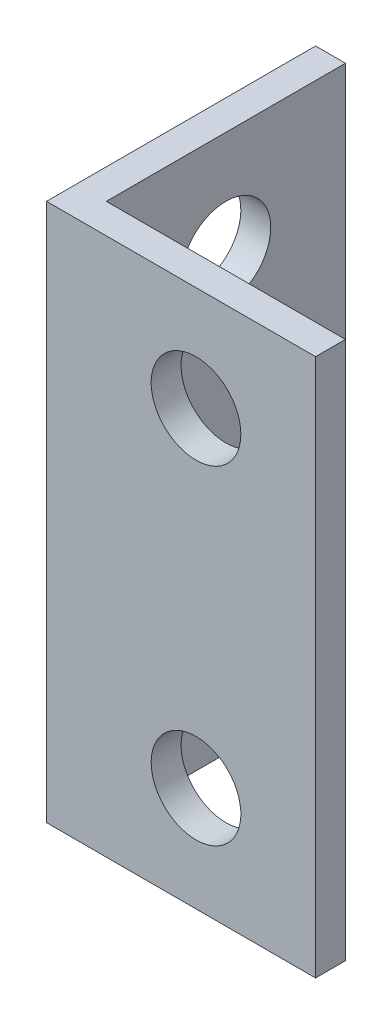
SolidWorks part; units mm, degrees
ref_plane "Plan de face" through (0, 0, 0) normal (0, 0, 1) x (1, 0, 0)
ref_plane "Plan de dessus" through (0, 0, 0) normal (0, 1, 0) x (1, 0, 0)
ref_plane "Plan de droite" through (0, 0, 0) normal (1, 0, 0) x (0, 0, -1)
sketch "Esquisse1" plane through (0, 0, 0) normal (0, 0, 1) x (1, 0, 0)
  line L0 (0, 10.3156) -> (0, -3.6144) construction
  line L1 (-4, 18) -> (4, 18)
  line L2 (-4, 18) -> (-4, 0)
  line L3 (-4, 0) -> (4, 0)
  line L4 (4, 18) -> (4, 0)
  dimension "D1" = 8
  dimension "D2" = 18
extrude "Boss.-Extru.1" add sketch "Esquisse1" along normal blind 1
sketch "Esquisse2" plane through (0, 0, 1) normal (0, 0, 1) x (1, 0, 0)
  line L1 (-4, 18) -> (-5, 18)
  line L2 (-4, 18) -> (-4, 0)
  line L3 (-4, 0) -> (-5, 0)
  line L4 (-5, 18) -> (-5, 0)
  dimension "D1" = 1
extrude "Boss.-Extru.2" add sketch "Esquisse2" against normal blind 9
sketch "Esquisse3" plane through (-4, 0, 0) normal (1, 0, 0) x (0, 0, -1)
  line L0 (4, 18) -> (4, -3.6029) construction
  line L1 (8, 18) -> (0, 18) construction
  line L2 (8, 9) -> (0, 9) construction
  line L3 (8, 0) -> (8, 18) construction
  line L4 (0, 0) -> (0, 18) construction
  circle A0 centre (4, 14.5) radius 1.5
  circle A1 centre (4, 3.5) radius 1.5
  dimension "D1" = 3
  dimension "D2" = 11
extrude "Enlèv. mat.-Extru.1" cut sketch "Esquisse3" against normal through all
sketch "Esquisse4" plane through (0, 0, 0) normal (0, 0, -1) x (-1, 0, 0)
  line L0 (0, 0) -> (0, 20.3938) construction
  line L1 (-4, 9) -> (5, 9) construction
  line L2 (-4, 0) -> (-4, 18) construction
  line L3 (5, 18) -> (5, 0) construction
  circle A0 centre (0, 3.5) radius 1.5
  circle A1 centre (0, 14.5) radius 1.5
  dimension "D2" = 3
  dimension "D1" = 11
extrude "Enlèv. mat.-Extru.2" cut sketch "Esquisse4" against normal through all
